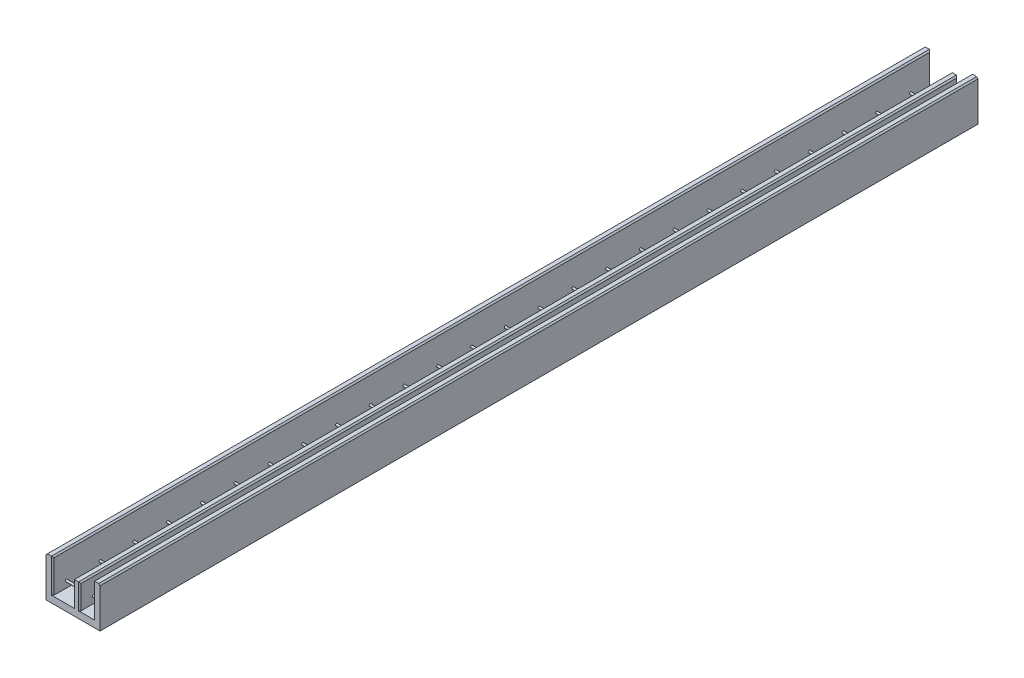
SolidWorks part; units mm, degrees
ref_plane "Alzado" through (0, 0, 0) normal (0, 0, 1) x (1, 0, 0)
ref_plane "Planta" through (0, 0, 0) normal (0, 1, 0) x (1, 0, 0)
ref_plane "Vista lateral" through (0, 0, 0) normal (1, 0, 0) x (0, 0, -1)
sketch "Croquis1" plane through (0, 0, 0) normal (0, 0, 1) x (1, 0, 0)
  line L0 (0, 0) -> (-800, 0)
  line L1 (-800, 0) -> (-800, 600)
  line L2 (-800, 600) -> (-700, 600)
  line L3 (-700, 600) -> (-700, 100)
  line L4 (-700, 100) -> (-400, 100)
  line L5 (-400, 100) -> (-400, 470)
  line L6 (-400, 470) -> (-300, 470)
  line L7 (-300, 470) -> (-300, 100)
  line L8 (-300, 100) -> (-100, 100)
  line L9 (-100, 100) -> (-100, 600)
  line L10 (-100, 600) -> (0, 600)
  line L11 (0, 600) -> (0, 0)
  dimension "D1" = 800
  dimension "D2" = 600
  dimension "D3" = 100
  dimension "D4" = 500
  dimension "D5" = 300
  dimension "D6" = 370
  dimension "D7" = 100
  dimension "D8" = 370
  dimension "D9" = 200
extrude "Saliente-Extruir1" add sketch "Croquis1" along normal blind 13000
chamfer "Chaflán2" distance 20 angle 45 14 edges at (-100, 350, 0) (0, 600, 6500) (-700, 350, 0) (-700, 600, 6500) (-700, 350, 13000) (-100, 350, 13000) (-300, 285, 0) (-300, 285, 13000) (-300, 470, 6500) (-400, 285, 0) (-400, 285, 13000) (-400, 470, 6500) (-800, 600, 6500) (-100, 600, 6500)
sketch "Croquis2" plane through (-800, 0, 0) normal (-1, 0, 0) x (0, 0, 1)
  line L0 (0, 580) -> (0, 0) construction
  circle A0 centre (300, 200) radius 15
  dimension "D3" = 30
  dimension "D1" = 300
extrude "Saliente-Extruir2" add sketch "Croquis2" against normal up to surface (700 mm away) up to face at (-100, 340, 6500)
pattern_linear "MatrizL1" count 26 spacing 500 along (0, 0, 1) of "Saliente-Extruir2"
